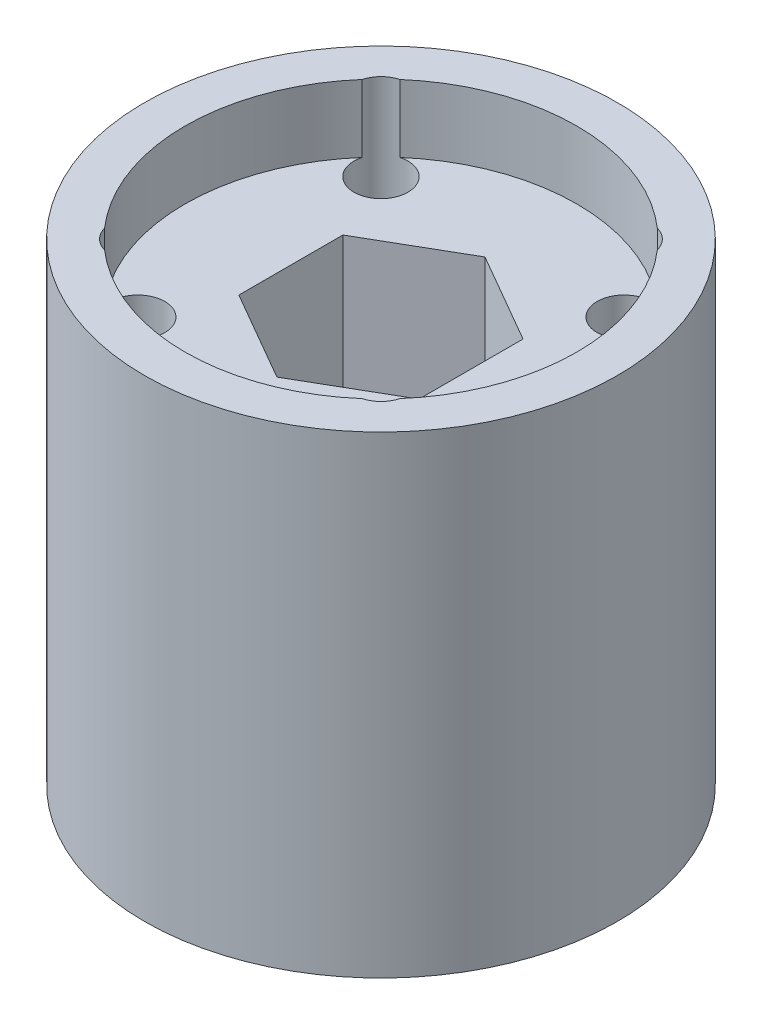
SolidWorks part; units mm, degrees
ref_plane "Спереди" through (0, 0, 0) normal (0, 0, 1) x (1, 0, 0)
ref_plane "Сверху" through (0, 0, 0) normal (0, 1, 0) x (1, 0, 0)
ref_plane "Справа" through (0, 0, 0) normal (1, 0, 0) x (0, 0, -1)
sketch "Sketch1" plane through (0, 0, 0) normal (0, 1, 0) x (1, 0, 0)
  line L1 (12.3744, -12.3744) -> (-12.3744, -12.3744) construction
  line L2 (12.3744, -12.3744) -> (12.3744, 12.3744) construction
  line L3 (12.3744, 12.3744) -> (-12.3744, 12.3744) construction
  line L4 (-12.3744, -12.3744) -> (-12.3744, 12.3744) construction
  line L5 (12.3744, -12.3744) -> (-12.3744, 12.3744) construction
  line L6 (12.3744, 12.3744) -> (-12.3744, -12.3744) construction
  circle A0 centre (0, 0) radius 17.5
  point P0 (0, 0)
  dimension "D1" = 35
extrude "Boss-Extrude1" add sketch "Sketch1" along normal blind 35
sketch "Sketch2" plane through (0, 35, 0) normal (0, 1, 0) x (1, 0, 0)
  line L1 (0, 7.7) -> (-6.6684, 3.85)
  line L2 (-6.6684, 3.85) -> (-6.6684, -3.85)
  line L3 (-6.6684, -3.85) -> (0, -7.7)
  line L4 (0, -7.7) -> (6.6684, -3.85)
  line L5 (6.6684, -3.85) -> (6.6684, 3.85)
  line L6 (6.6684, 3.85) -> (0, 7.7)
  circle A0 centre (0, 0) radius 7.7 construction
  dimension "D1" = 15.4
extrude "Cut-Extrude1" cut sketch "Sketch2" against normal blind 15
sketch "Sketch3" plane through (0, 20, 0) normal (0, 1, 0) x (1, 0, 0)
  circle A0 centre (0, 0) radius 4.1
  dimension "D1" = 8.2
extrude "Cut-Extrude2" cut sketch "Sketch3" against normal through all
sketch "Sketch4" plane through (0, 35, 0) normal (0, 1, 0) x (1, 0, 0)
  line L1 (9, -9) -> (-9, -9) construction
  line L2 (9, -9) -> (9, 9) construction
  line L3 (9, 9) -> (-9, 9) construction
  line L4 (-9, -9) -> (-9, 9) construction
  line L5 (9, -9) -> (-9, 9) construction
  line L6 (9, 9) -> (-9, -9) construction
  circle A0 centre (-9, 9) radius 2
  circle A1 centre (9, 9) radius 2
  circle A2 centre (9, -9) radius 2
  circle A3 centre (-9, -9) radius 2
  point P0 (0, 0)
  dimension "D1" = 4
  dimension "D2" = 18
extrude "Cut-Extrude3" cut sketch "Sketch4" against normal through all
sketch "Sketch5" plane through (0, 35, 0) normal (0, 1, 0) x (1, 0, 0)
  circle A0 centre (0, 0) radius 14.5
  circle A1 centre (0, 0) radius 17.5 construction
  dimension "D1" = 3
extrude "Cut-Extrude4" cut sketch "Sketch5" against normal blind 5
